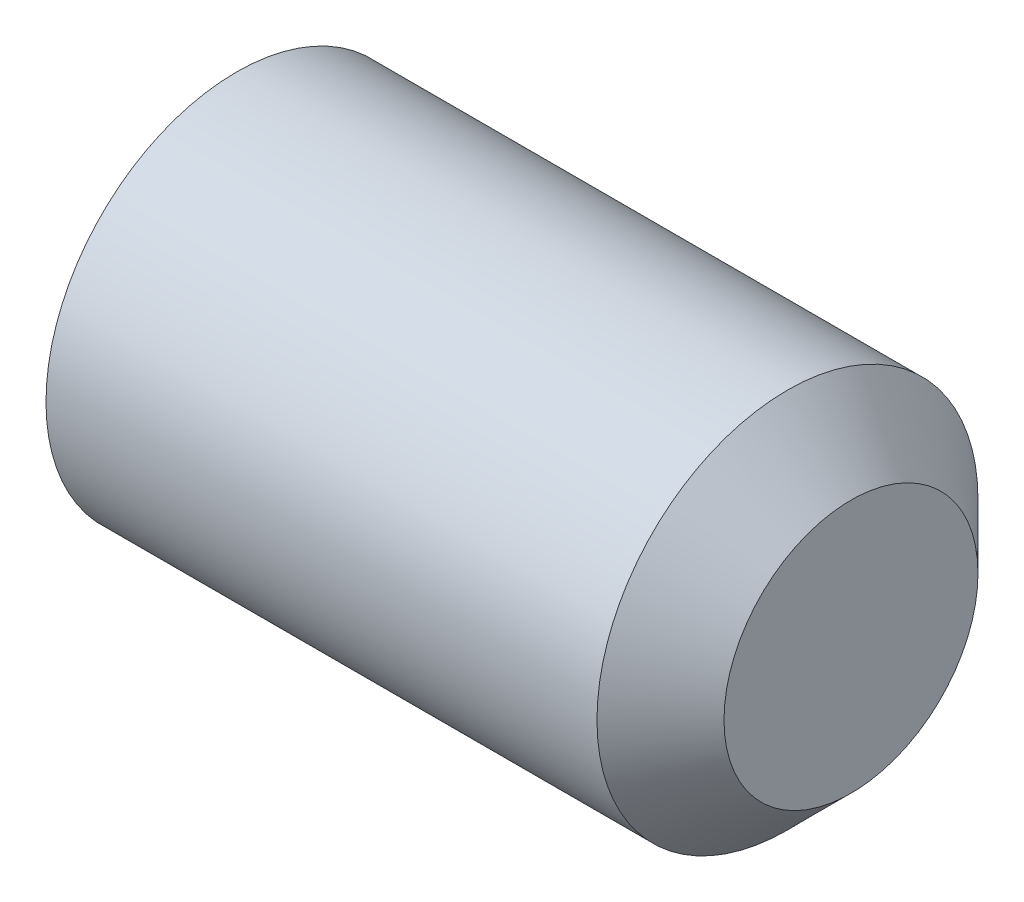
SolidWorks part; units mm, degrees
ref_plane "Face" through (0, 0, 0) normal (0, 0, 1) x (1, 0, 0)
ref_plane "Dessus" through (0, 0, 0) normal (0, 1, 0) x (1, 0, 0)
ref_plane "Droite" through (0, 0, 0) normal (1, 0, 0) x (0, 0, -1)
ref_plane "Plan1" through (0, 0, 0) normal (0, 0, -1) x (-1, 0, 0)
sketch "Esquisse1" plane through (0, 0, 0) normal (0, 0, -1) x (-1, 0, 0)
  line L0 (-5, 1.5) -> (-5, 0)
  line L1 (-5, 0) -> (0, 0)
  line L2 (0, 0) -> (0, 1.5)
  line L3 (0, 1.5) -> (-5, 1.5)
  line L4 (-5, 0) -> (0, 0) construction
revolve "Révolution1" add sketch "Esquisse1" angle 360 about L4
sketch "Esquisse2" plane through (0, 0, 0) normal (-1, 0, 0) x (0, 0, 1)
  line L0 (0.433, -0.75) -> (0.866, 0)
  line L1 (0.866, 0) -> (0.433, 0.75)
  line L2 (0.433, 0.75) -> (-0.433, 0.75)
  line L3 (-0.433, 0.75) -> (-0.866, 0)
  line L4 (-0.866, 0) -> (-0.433, -0.75)
  line L5 (-0.433, -0.75) -> (0.433, -0.75)
extrude "Enlèv. mat.-Extru.1" cut sketch "Esquisse2" against normal blind 2
chamfer "Chanfrein1" distance 0.5 angle 45 1 edges at (5, 0, 1.5)
chamfer "Chanfrein2" distance 0.2805 angle 30 1 edges at (0, 0, 1.5)
